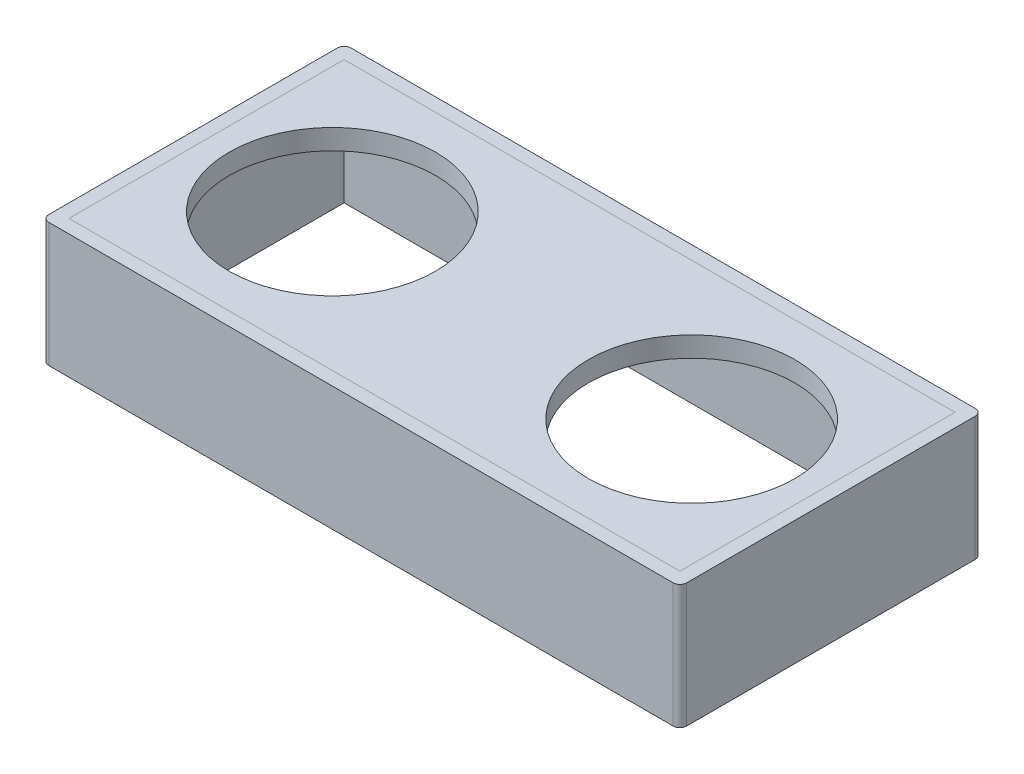
SolidWorks part; units mm, degrees
ref_plane "Front" through (0, 0, 0) normal (0, 0, 1) x (1, 0, 0)
ref_plane "Top" through (0, 0, 0) normal (0, 1, 0) x (1, 0, 0)
ref_plane "Right" through (0, 0, 0) normal (1, 0, 0) x (0, 0, -1)
sketch "Croquis2" plane through (0, 0, 0) normal (0, 1, 0) x (1, 0, 0)
  line L0 (-21.7519, -9.7231) -> (23.5481, -9.7231)
  line L1 (23.5481, -9.7231) -> (23.5481, 10.6769)
  line L2 (23.5481, 10.6769) -> (-21.7519, 10.6769)
  line L3 (-21.7519, 10.6769) -> (-21.7519, -9.7231)
  circle A0 centre (14.2181, 0.4769) radius 7.65
  circle A1 centre (-12.4219, 0.4769) radius 7.65
  point P8 (0, 0)
  dimension "D1" = 15.3
  dimension "D2" = 15.3
  dimension "D3" = 26.64
  dimension "D4" = 20.4
  dimension "D5" = 45.3
  dimension "D6" = 9.33
extrude "Saliente-Extruir1" add sketch "Croquis2" along normal blind 1.5
sketch "Croquis3" plane through (0, 0, 0) normal (0, -1, 0) x (1, 0, 0)
  line L8 (-22.7519, 10.7231) -> (-22.7519, -11.6769)
  line L9 (-22.7519, -11.6769) -> (24.5481, -11.6769)
  line L10 (24.5481, -11.6769) -> (24.5481, 10.7231)
  line L11 (24.5481, 10.7231) -> (-22.7519, 10.7231)
  line L12 (-22.7519, 10.2231) -> (-22.7519, -11.1769)
  line L13 (-22.2519, -11.6769) -> (24.0481, -11.6769)
  line L14 (24.5481, -11.1769) -> (24.5481, 10.2231)
  line L15 (24.0481, 10.7231) -> (-22.2519, 10.7231)
  line L16 (-21.7519, 9.7231) -> (-21.7519, -10.6769)
  line L17 (-21.7519, -10.6769) -> (23.5481, -10.6769)
  line L18 (23.5481, -10.6769) -> (23.5481, 9.7231)
  line L19 (23.5481, 9.7231) -> (-21.7519, 9.7231)
  line L20 (-21.7519, 9.7231) -> (-21.7519, -10.6769)
  line L21 (-21.7519, -10.6769) -> (23.5481, -10.6769)
  line L22 (23.5481, -10.6769) -> (23.5481, 9.7231)
  line L23 (23.5481, 9.7231) -> (-21.7519, 9.7231)
  arc A0 (24.5481, 10.2231) -> (24.0481, 10.7231) centre (24.0481, 10.2231) ccw
  arc A1 (24.0481, -11.6769) -> (24.5481, -11.1769) centre (24.0481, -11.1769) ccw
  arc A2 (-22.7519, -11.1769) -> (-22.2519, -11.6769) centre (-22.2519, -11.1769) ccw
  arc A3 (-22.7519, 10.2231) -> (-22.2519, 10.7231) centre (-22.2519, 10.2231) cw
  dimension "D3" = 0.5
  dimension "D1" = 1
  dimension "D2" = 0
extrude "Saliente-Extruir2" add sketch "Croquis3" along normal blind 7.7 and the other way up to surface (1.5 mm away) separate body other way up to face at (14.2181, 1.5, 7.1731)
